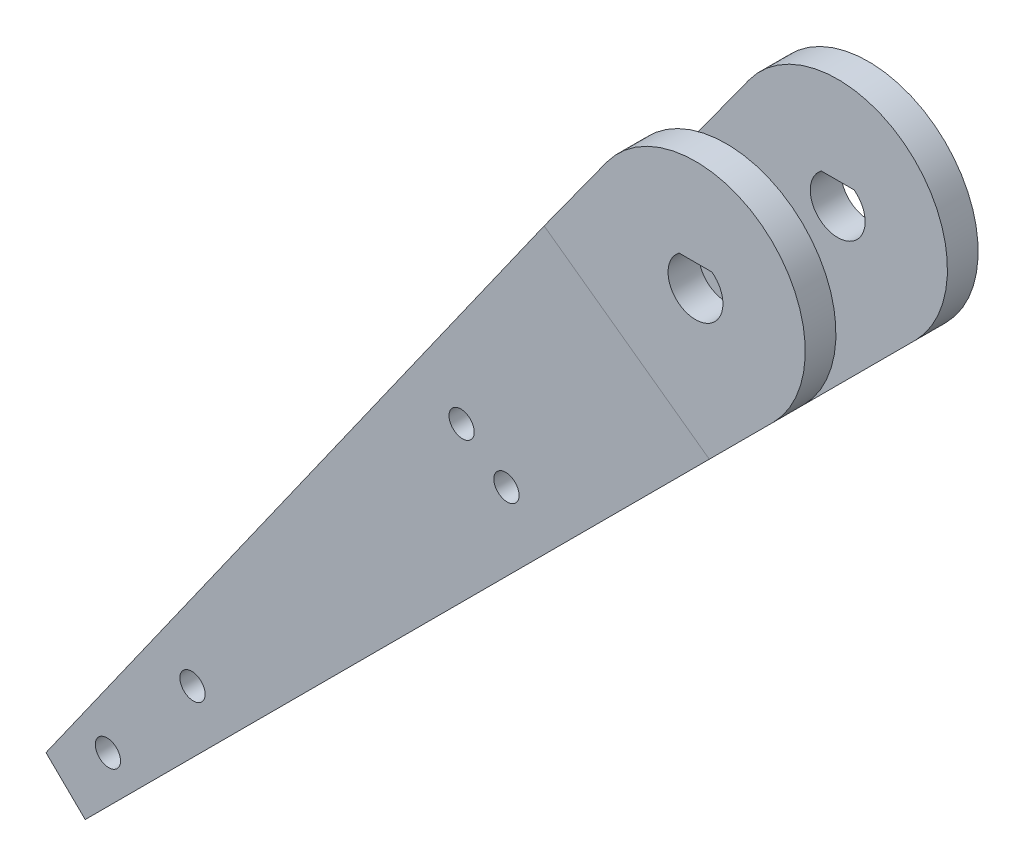
SolidWorks part; units mm, degrees
ref_plane "Front Plane" through (0, 0, 0) normal (0, 0, 1) x (1, 0, 0)
ref_plane "Top Plane" through (0, 0, 0) normal (0, 1, 0) x (1, 0, 0)
ref_plane "Right Plane" through (0, 0, 0) normal (1, 0, 0) x (0, 0, -1)
sketch "Sketch9" plane through (0, 0, 0) normal (0, 0, 1) x (1, 0, 0)
  line L0 (-2.2451, 2.2451) -> (2.2451, -2.2451)
  line L1 (2.2451, -2.2451) -> (86.8302, 82.34)
  line L2 (67.5592, 98.7628) -> (-2.2451, 2.2451)
  line L3 (-8.0191, 0) -> (8.0191, 0) construction
  arc A0 (86.8302, 82.34) -> (67.5592, 98.7628) centre (77.8499, 91.3203) ccw
  point P4 (0, 0)
  point P9 (0, 0)
  point P10 (8.0191, 0)
  point P11 (1.3091, -1.3091)
  point P12 (106.567, 55.1678)
  point P13 (103.8204, 60.9692)
  point P14 (88.0875, 81.253)
  point P15 (-3.2125, 3.2125)
  dimension "D2" = 12.7
  dimension "D1" = 45
  dimension "D3" = 120
  dimension "D4" = 6.35
extrude "base_volume" add sketch "Sketch9" against normal blind 10
sketch "Sketch10" plane through (-2.5401, 1.8371, 0) normal (-0.8103, 0.586, 0) x (0, 0, 1)
  line L0 (-10, 107.3) -> (-10, -0.5035)
  line L1 (-10, 119.6182) -> (-10, 0.5035) construction
  line L2 (-10, -0.5035) -> (-5, -0.5035)
  line L3 (-10, -0.5035) -> (0, -0.5035) construction
  line L4 (-5, -0.5035) -> (-10, 107.3)
  line L5 (0, 132.3182) -> (-6.45, 132.3182)
  line L7 (-6.45, 132.3182) -> (-6.45, 92.3182)
  line L9 (0, 119.6182) -> (0, 0.5035) construction
  line L10 (0, 32.3182) -> (0, 132.3182)
  line L11 (-6.45, 92.3182) -> (0, 92.3182) construction
  line L12 (-6.45, 92.3182) -> (-3.225, 32.3182)
  line L13 (-3.225, 32.3182) -> (0, 32.3182)
  line L14 (-5.9491, 83) -> (0, 83)
  line L15 (-5.6266, 77) -> (0, 77)
  line L16 (-2.9746, 83) -> (-2.9746, 77) construction
  line L17 (-10, 0) -> (-5.0234, 0) construction
  point P9 (-5, -0.5035)
  point P13 (-3.225, 92.3182)
  point P25 (-2.9746, 80)
  point P29 (-6.35, -0.5035)
  line M9 (0, 0.5035) -> (0, 119.6182)
  line M10 (0, 119.6182) -> (-10, 119.6182)
  line M11 (-10, 119.6182) -> (-10, 0.5035)
  line M12 (-10, 0.5035) -> (0, 0.5035)
  dimension "D1" = 107.3
  dimension "D2" = 6.45
  dimension "D3" = 40
  dimension "D4" = 100
  dimension "D5" = 6
  dimension "D6" = 80
extrude "weight_saving" cut sketch "Sketch10" against normal up to next contours L15 L12 L13 M9 | L12 L14 L10 L7 M10 | L4 M12 M11 | L10 L5 L7 M10
sketch "Sketch11" plane through (0, 0, -6.45) normal (0, 0, 1) x (1, 0, 0)
  line L0 (75.9549, 93.8677) -> (79.7449, 93.8677)
  arc A0 (75.9549, 93.8677) -> (79.7449, 93.8677) centre (77.8499, 91.3203) ccw
  arc A1 (86.8302, 82.34) -> (67.5592, 98.7628) centre (77.8499, 91.3203) ccw construction
  dimension "D1" = 6.35
  dimension "D2" = 3.79
extrude "D-shaft_hole" cut sketch "Sketch11" against normal up to next
mirror "Mirror1" about plane through (0, 0, 0) normal (0, 0, 1) of "D-shaft_hole", "weight_saving", "base_volume"
sketch "Sketch15" plane through (0, 0, 0) normal (0, 0, 1) x (1, 0, 0)
  line L0 (0, 0) -> (5.2688, 6.1606) construction
  line L1 (-2.2451, 2.2451) -> (2.2451, -2.2451) construction
  line L2 (5.2688, 6.1606) -> (10.5375, 12.3213) construction
  line L3 (10.5375, 12.3213) -> (15.8063, 18.4819) construction
  line L4 (15.8063, 18.4819) -> (21.075, 24.6425) construction
  line L5 (25.7509, 21.2608) -> (16.3992, 28.0243) construction
  line L6 (44.3419, 66.6605) -> (49.5277, 62.91) construction
  line L7 (-2.2451, 2.2451) -> (60.3404, 88.7815) construction
  line L8 (49.5277, 62.91) -> (54.7134, 59.1595) construction
  line L9 (54.7134, 59.1595) -> (59.8992, 55.4091) construction
  line L10 (2.2451, -2.2451) -> (79.4506, 74.9605) construction
  line L11 (57.7507, 53.2605) -> (62.0477, 57.5576) construction
  line L12 (46.1, 69.0914) -> (42.5838, 64.2296) construction
  circle A0 centre (5.2688, 6.1606) radius 1.5
  circle A2 centre (15.8063, 18.4819) radius 1.5
  circle A3 centre (49.5277, 62.91) radius 1.5
  circle A4 centre (54.7134, 59.1595) radius 1.5
  point P23 (59.8992, 55.4091)
  point P29 (44.3419, 66.6605)
  dimension "D1" = 3
extrude "trous_m3" cut sketch "Sketch15" against normal through all both and the other way through all
